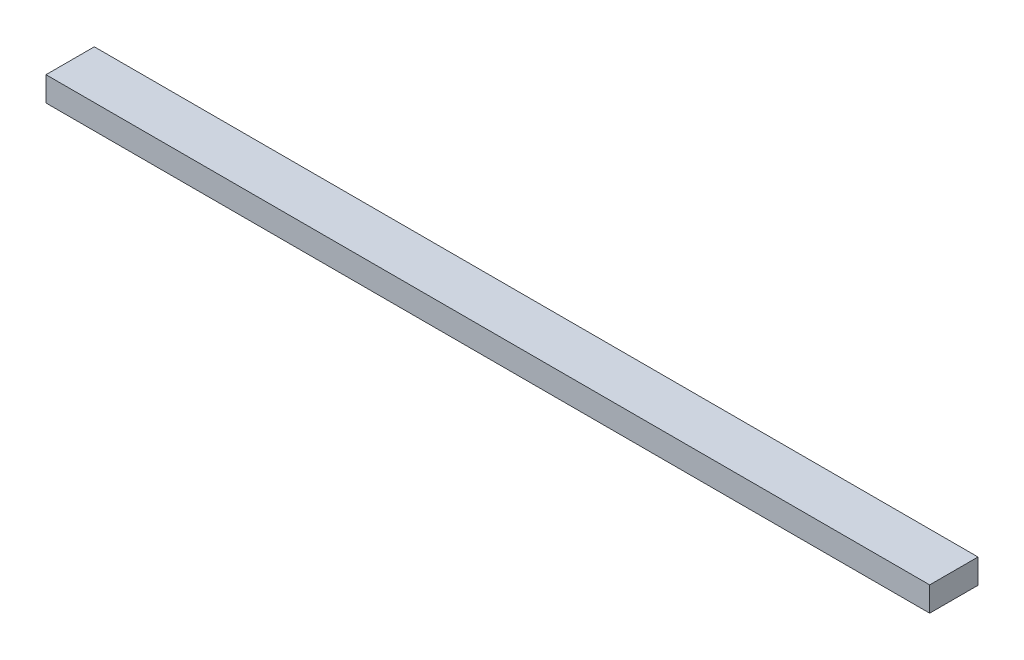
SolidWorks part; units mm, degrees
ref_plane "Front Plane" through (0, 0, 0) normal (0, 0, 1) x (1, 0, 0)
ref_plane "Top Plane" through (0, 0, 0) normal (0, 1, 0) x (1, 0, 0)
ref_plane "Right Plane" through (0, 0, 0) normal (1, 0, 0) x (0, 0, -1)
sketch "Sketch1" plane through (0, 0, 0) normal (0, 0, 1) x (1, 0, 0)
  line L0 (-0.254, 0.254) -> (18.034, 0.254)
  line L1 (18.034, 0.254) -> (18.034, -0.254)
  line L2 (18.034, -0.254) -> (-0.254, -0.254)
  line L3 (-0.254, -0.254) -> (-0.254, 0.254)
extrude "Component_Outline" add sketch "Sketch1" along normal blind 1 separate body
sketch3d "3DSketch1"
  line L0 (0, 0, 0) -> (1, 0, 0)
  line L1 (0, 0, 0) -> (0, 1, 0)
  line L2 (0, 0, 0) -> (0, 0, 1)
  point P0 (0, 0, 0)
